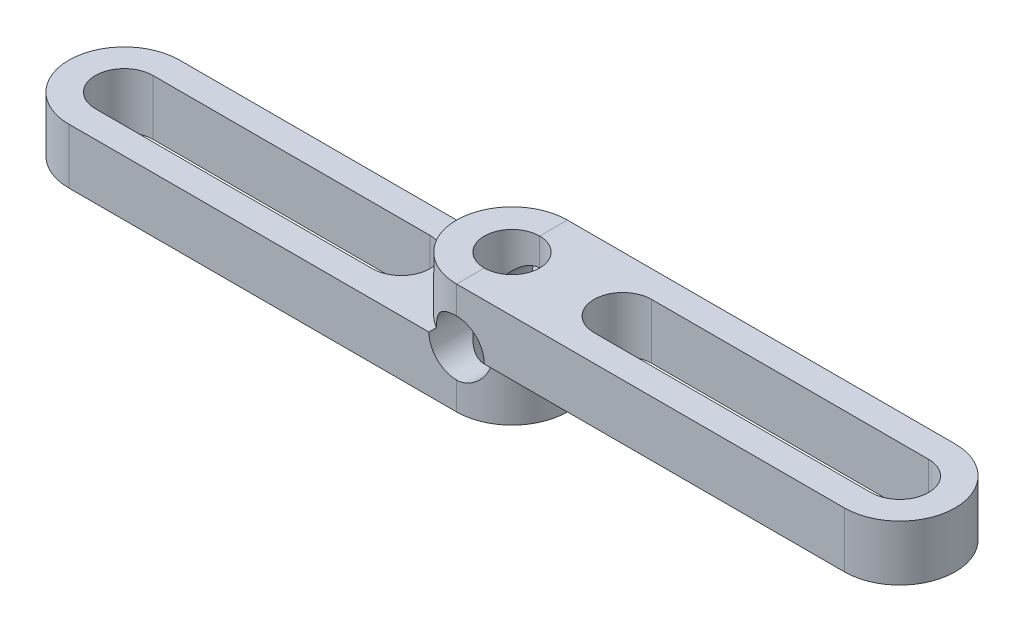
SolidWorks part; units mm, degrees
ref_plane "Front Plane" through (0, 0, 0) normal (0, 0, 1) x (1, 0, 0)
ref_plane "Top Plane" through (0, 0, 0) normal (0, 1, 0) x (1, 0, 0)
ref_plane "Right Plane" through (0, 0, 0) normal (1, 0, 0) x (0, 0, -1)
sketch "Sketch1" plane through (0, 0, 0) normal (0, 1, 0) x (1, 0, 0)
  line L1 (0, 6.35) -> (-44.45, 6.35)
  line L2 (0, 6.35) -> (0, -6.35)
  line L3 (0, -6.35) -> (-44.45, -6.35)
  line L4 (-44.45, 6.35) -> (-44.45, -6.35) construction
  arc A0 (-44.45, 6.35) -> (-44.45, -6.35) centre (-44.45, 0) ccw
  point P4 (0, 0)
  point P5 (0, 0)
  dimension "D1" = 44.45
  dimension "D2" = 12.7
extrude "Boss-Extrude1" add sketch "Sketch1" along normal blind 6.35
sketch "Sketch2" plane through (0, 6.35, 0) normal (0, 1, 0) x (1, 0, 0)
  line L0 (0, 6.35) -> (-44.45, 6.35) construction
  line L1 (0, 6.35) -> (44.45, 6.35)
  line L2 (0, 6.35) -> (0, -6.35)
  line L3 (0, -6.35) -> (44.45, -6.35)
  line L4 (44.45, 6.35) -> (44.45, -6.35) construction
  line L5 (-44.45, -6.35) -> (0, -6.35) construction
  arc A0 (44.45, 6.35) -> (44.45, -6.35) centre (44.45, 0) cw
  point P11 (0, 0)
  dimension "D2" = 44.45
extrude "Boss-Extrude2" add sketch "Sketch2" along normal blind 6.35
sketch "Sketch4" plane through (0, 12.7, 0) normal (0, 1, 0) x (1, 0, 0)
  line L0 (-44.45, 0) -> (-12.7, 0) construction
  line L1 (-44.45, 3.302) -> (-12.7, 3.302)
  line L2 (-44.45, -3.302) -> (-12.7, -3.302)
  line L3 (44.45, 0) -> (12.7, 0) construction
  line L4 (44.45, -3.302) -> (12.7, -3.302)
  line L5 (44.45, 3.302) -> (12.7, 3.302)
  arc A4 (-44.45, 3.302) -> (-44.45, -3.302) centre (-44.45, 0) ccw
  arc A5 (-12.7, -3.302) -> (-12.7, 3.302) centre (-12.7, 0) ccw
  arc A6 (-44.45, 6.35) -> (-44.45, -6.35) centre (-44.45, 0) ccw construction
  arc A7 (44.45, -3.302) -> (44.45, 3.302) centre (44.45, 0) ccw
  arc A8 (12.7, 3.302) -> (12.7, -3.302) centre (12.7, 0) ccw
  arc A9 (44.45, -6.35) -> (44.45, 6.35) centre (44.45, 0) ccw construction
  point P4 (-28.575, 0)
  point P7 (28.575, 0)
  dimension "D1" = 3.302
  dimension "D2" = 31.75
sketch "Sketch5" plane through (0, 6.35, 0) normal (0, 1, 0) x (1, 0, 0)
  line L1 (0, 6.35) -> (0, -6.35)
  line L2 (0, -6.35) -> (0, 6.35) construction
  line L3 (0, 6.35) -> (-44.45, 6.35) construction
  arc A0 (0, 6.35) -> (0, -6.35) centre (0, 0) ccw
  point P3 (0, 0)
extrude "Boss-Extrude3" add sketch "Sketch5" along normal up to surface (6.35 mm away) up to face at (23.8125, 12.7, 0)
sketch "Sketch6" plane through (0, 0, 0) normal (0, -1, 0) x (1, 0, 0)
  line L0 (0, 6.35) -> (0, -6.35)
  arc A0 (0, 6.35) -> (0, -6.35) centre (0, 0) cw
extrude "Boss-Extrude4" add sketch "Sketch6" against normal up to surface (6.35 mm away) up to face at (23.8125, 6.35, 0)
extrude "Cut-Extrude3" cut sketch "Sketch4" against normal through all
sketch "Sketch9" plane through (0, 0, 6.35) normal (0, 0, 1) x (1, 0, 0)
  circle A0 centre (0, 6.35) radius 3.175
  dimension "D1" = 6.35
extrude "Cut-Extrude5" cut sketch "Sketch9" against normal through all
sketch "Sketch10" plane through (0, 12.7, 0) normal (0, 1, 0) x (1, 0, 0)
  circle A0 centre (0, 0) radius 3.175
  dimension "D1" = 6.35
extrude "Cut-Extrude6" cut sketch "Sketch10" against normal through all
